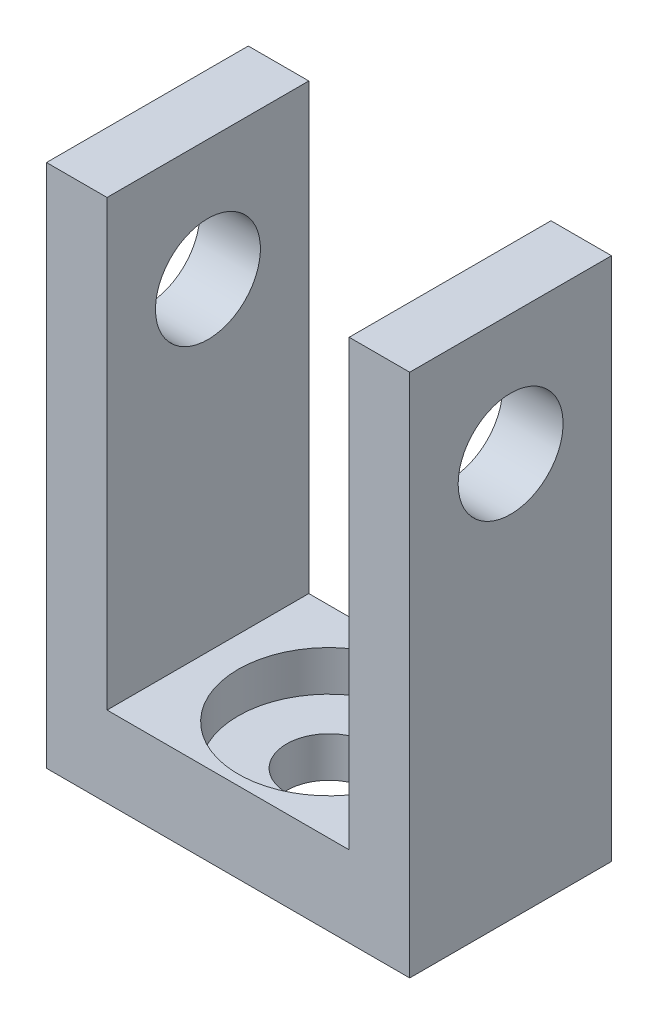
SolidWorks part; units mm, degrees
ref_plane "Front Plane" through (0, 0, 0) normal (0, 0, 1) x (1, 0, 0)
ref_plane "Top Plane" through (0, 0, 0) normal (0, 1, 0) x (1, 0, 0)
ref_plane "Right Plane" through (0, 0, 0) normal (1, 0, 0) x (0, 0, -1)
sketch "Sketch1" plane through (0, 0, 0) normal (0, 0, 1) x (1, 0, 0)
  line L0 (-6, 0) -> (6, 0)
  line L1 (-6, 0) -> (-6, 22)
  line L2 (6, 0) -> (6, 22)
  line L3 (9, -3) -> (9, 22)
  line L4 (-9, -3) -> (9, -3)
  line L5 (-9, -3) -> (-9, 22)
  line L6 (6, 22) -> (9, 22)
  line L7 (-6, 22) -> (-9, 22)
  point P4 (0, 0)
  dimension "D1" = 12
  dimension "D2" = 22
  dimension "D3" = 3
extrude "Boss-Extrude1" add sketch "Sketch1" along normal blind 10
sketch "Sketch2" plane through (-9, 0, 0) normal (-1, 0, 0) x (0, 0, 1)
  line L0 (5, 16) -> (5, 22)
  line L1 (10, 22) -> (0, 22) construction
  circle A0 centre (5, 16) radius 2.6
  dimension "D1" = 5.2
  dimension "D2" = 6
extrude "Cut-Extrude4" cut sketch "Sketch2" against normal blind 25
sketch "Sketch5" plane through (0, -3, 0) normal (0, -1, 0) x (1, 0, 0)
  line L0 (-9, 5) -> (9, 5)
  line L1 (-9, 10) -> (-9, 0) construction
  line L2 (9, 10) -> (9, 0) construction
  line L3 (0, 10) -> (0, 5)
  line L4 (-9, 10) -> (9, 10) construction
  circle A0 centre (0, 5) radius 2.1
  dimension "D1" = 4.2
extrude "Cut-Extrude5" cut sketch "Sketch5" against normal blind 10 contours L0 A0 | L0 A0 L3 | L3 A0 L0
sketch "Sketch6" plane through (0, 0, 0) normal (0, 1, 0) x (1, 0, 0)
  circle A0 centre (0, -5) radius 4.5
  dimension "D1" = 9
extrude "Cut-Extrude6" cut sketch "Sketch6" against normal blind 2
sketch "Sketch7" plane through (0, -3, 0) normal (0, -1, 0) x (1, 0, 0)
  line L4 (-9, 0) -> (9, 0)
  line L5 (9, 0) -> (9, 10)
  line L6 (9, 10) -> (-9, 10)
  line L7 (-9, 10) -> (-9, 0)
  line L8 (-9, 0) -> (9, 0)
  line L9 (9, 0) -> (9, 10)
  line L10 (9, 10) -> (-9, 10)
  line L11 (-9, 10) -> (-9, 0)
  circle A0 centre (0, 5) radius 2.1 construction
  circle A1 centre (0, 5) radius 2.1
  dimension "D1" = 0
extrude "Boss-Extrude2" add sketch "Sketch7" along normal blind 1
